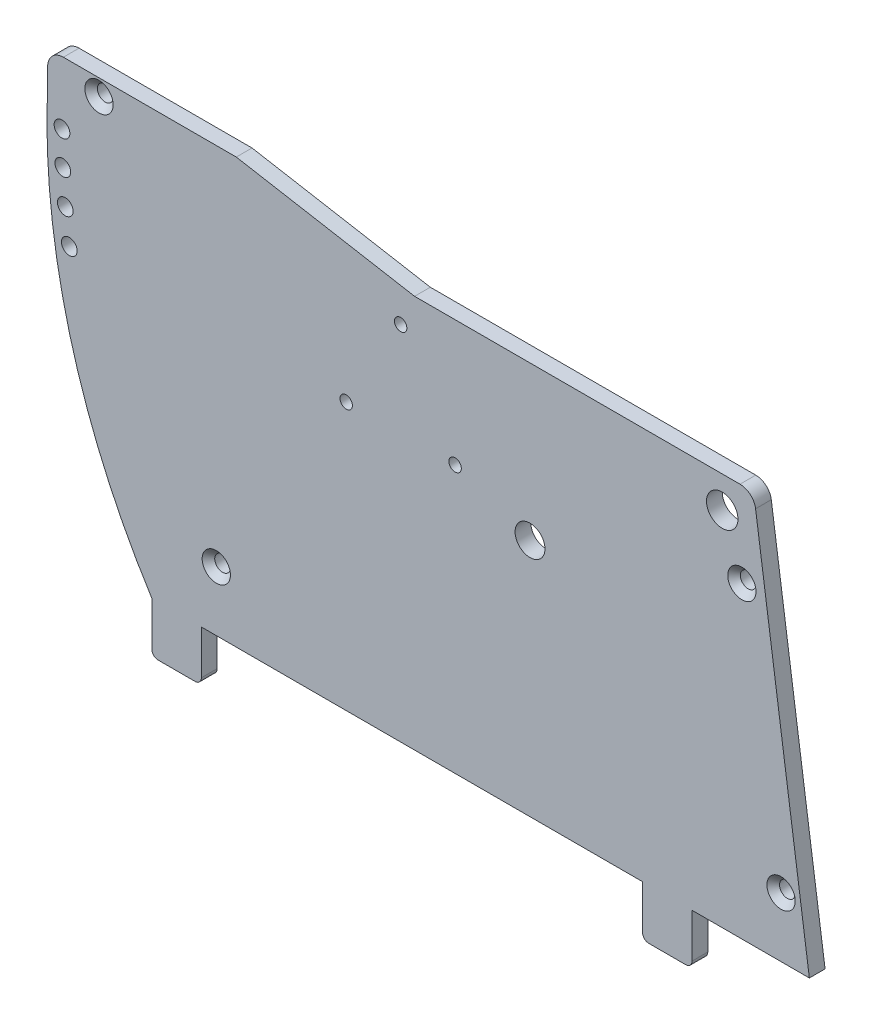
SolidWorks part; units mm, degrees
ref_plane "Front Plane" through (0, 0, 0) normal (0, 0, 1) x (1, 0, 0)
ref_plane "Top Plane" through (0, 0, 0) normal (0, 1, 0) x (1, 0, 0)
ref_plane "Right Plane" through (0, 0, 0) normal (1, 0, 0) x (0, 0, -1)
sketch "Sketch18" plane through (0, 0, 0) normal (0, 0, 1) x (1, 0, 0)
  line L0 (0, 0) -> (-265.6047, 0)
  line L1 (-165.1, 120.65) -> (-165.1, 146.05) construction
  line L4 (0, 0) -> (-21.7272, 153.2911)
  line L5 (-28.0144, 158.75) -> (-159.4738, 158.75)
  line L6 (-159.4738, 158.75) -> (-231.4991, 171.45)
  line L7 (-231.4991, 171.45) -> (-301.3491, 171.45)
  line L8 (-307.6991, 165.1) -> (-307.6991, 158.75)
  circle A0 centre (-35.2009, 146.05) radius 266.7 construction
  arc A1 (-307.6991, 158.75) -> (-265.6047, 0) centre (-35.2009, 146.05) ccw
  arc A2 (-21.7272, 153.2911) -> (-28.0144, 158.75) centre (-28.0144, 152.4) ccw
  arc A3 (-301.3491, 171.45) -> (-307.6991, 165.1) centre (-301.3491, 165.1) ccw
  circle A4 centre (-11.4235, 24.0347) radius 3.175
  circle A5 centre (-27.2534, 124.4065) radius 3.175
  circle A6 centre (-35.2009, 146.05) radius 6.35
  circle A7 centre (-301.9009, 146.05) radius 3.175
  circle A8 centre (-301.5697, 132.7614) radius 3.175
  circle A9 centre (-300.5799, 119.5375) radius 3.175
  circle A10 centre (-298.9435, 106.4428) radius 3.175
  circle A11 centre (-239.5689, 24.0347) radius 3.175
  circle A12 centre (-286.9621, 164.8507) radius 3.175
  circle A13 centre (-165.1, 146.05) radius 2.5019
  circle A14 centre (-143.103, 107.95) radius 2.5019
  circle A15 centre (-165.1, 120.65) radius 1.5875 construction
  circle A16 centre (-187.097, 107.95) radius 2.5019
  point P40 (-165.1, 120.65)
  dimension "D7" = 13.2886
  dimension "D8" = 13.2239
  dimension "D9" = 13.0947
  dimension "D10" = 5.0038
  dimension "D11" = 6.35
  dimension "D12" = 20.7369
  dimension "D16" = 6.35
  dimension "D17" = 6.35
  dimension "D18" = 25.4
  dimension "D19" = 3
  dimension "D5" = 3.175
  dimension "D2" = 158.75
  dimension "D3" = 81.933
  dimension "D4" = 12.7
  dimension "D6" = 25.4
  dimension "D13" = 6.5993
  dimension "D14" = 76.2
  dimension "D15" = 72.0253
extrude "Boss-Extrude4" add sketch "Sketch18" along normal blind 6.35 separate body
chamfer "Chamfer1" distance 2.54 angle 45 4 edges at (-283.7871, 164.8507, 6.35) (-236.3939, 24.0347, 6.35) (-8.2485, 24.0347, 6.35) (-24.0784, 124.4065, 6.35)
sketch "Sketch19" plane through (0, 0, 0) normal (0, 0, -1) x (-1, 0, 0)
  circle A1 centre (112.8435, 96.6743) radius 6.0325
  dimension "D1" = 12.065
extrude "Cut-Extrude1" cut sketch "Sketch19" against normal blind 43.434
sketch "Sketch20" plane through (0, 0, 0) normal (0, -1, 0) x (1, 0, 0)
  line L0 (-265.6047, 6.35) -> (0, 6.35) construction
  line L1 (-265.6047, 0) -> (-245.6047, 0)
  line L2 (-265.6047, 0) -> (-265.6047, 6.35)
  line L3 (-265.6047, 6.35) -> (-245.6047, 6.35)
  line L4 (-245.6047, 0) -> (-245.6047, 6.35)
  line L5 (-245.6047, 6.35) -> (-245.6047, 0) construction
  line L6 (-47.3848, 6.35) -> (-47.3848, 0) construction
  line L7 (-47.3848, 6.35) -> (-67.3848, 6.35)
  line L8 (-47.3848, 6.35) -> (-47.3848, 0)
  line L9 (-47.3848, 0) -> (-67.3848, 0)
  line L10 (-67.3848, 6.35) -> (-67.3848, 0)
  line L11 (-265.6047, 0) -> (0, 0) construction
  line L12 (-67.3848, 0) -> (-67.3848, 6.35) construction
extrude "Boss-Extrude5" add sketch "Sketch20" along normal blind 20.32
fillet "Fillet1" radius 2.54 4 edges at (-265.6047, -20.32, 3.175) (-245.6047, -20.32, 3.175) (-67.3848, -20.32, 3.175) (-47.3848, -20.32, 3.175)
